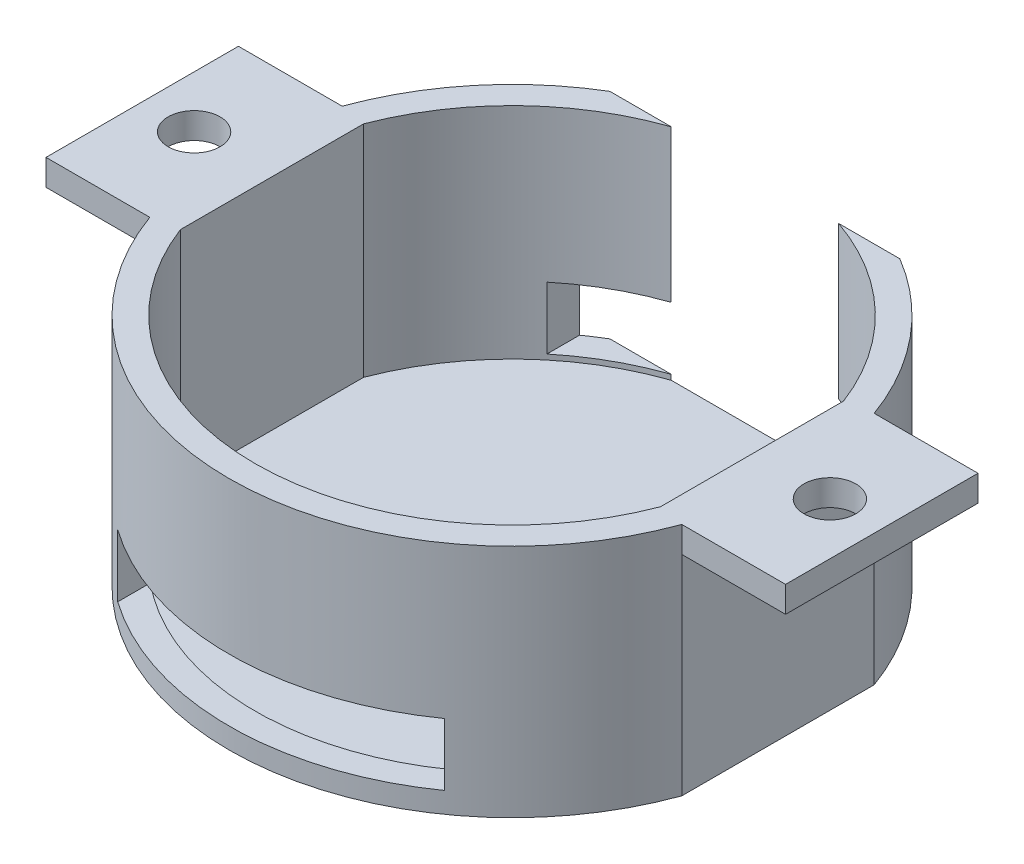
SolidWorks part; units mm, degrees
ref_plane "前视基准面" through (0, 0, 0) normal (0, 0, 1) x (1, 0, 0)
ref_plane "上视基准面" through (0, 0, 0) normal (0, 1, 0) x (1, 0, 0)
ref_plane "右视基准面" through (0, 0, 0) normal (1, 0, 0) x (0, 0, -1)
other "Configuration Table"
sketch "草图1" plane through (0, 0, 0) normal (0, 1, 0) x (1, 0, 0)
  line L0 (0, 0) -> (0, 49.5) construction
  line L1 (-46.25, 17.6405) -> (-46.25, -17.6405)
  line L2 (46.25, 17.6405) -> (46.25, -17.6405)
  line L3 (-51.25, 18.5388) -> (-51.25, -18.5388)
  line L4 (51.25, 18.5388) -> (51.25, -18.5388)
  arc A0 (-51.25, -18.5388) -> (51.25, -18.5388) centre (0, 0) ccw
  arc A1 (-46.25, -17.6405) -> (46.25, -17.6405) centre (0, 0) ccw
  arc A2 (46.25, 17.6405) -> (-46.25, 17.6405) centre (0, 0) ccw
  arc A3 (51.25, 18.5388) -> (-51.25, 18.5388) centre (0, 0) ccw
  dimension "D1" = 109
  dimension "D2" = 99
  dimension "D3" = 92.5
  dimension "D4" = 102.5
extrude "凸台-拉伸1" add sketch "草图1" along normal blind 42.3
ref_plane "基准面1" through (0, 0, 0) normal (0, -1, 0) x (-1, 0, 0)
sketch "草图2" plane through (0, 0, 0) normal (0, -1, 0) x (-1, 0, 0)
  line L0 (51.25, 18.5388) -> (51.25, -18.5388)
  line L1 (0, 54.5) -> (0, 0) construction
  line L2 (-51.25, 18.5388) -> (-51.25, -18.5388)
  circle A0 centre (0, 0) radius 54.5
  dimension "D1" = 109
extrude "凸台-拉伸2" add sketch "草图2" along normal blind 3
ref_plane "基准面3" through (-51.25, 0, 0) normal (-1, 0, 0) x (0, 0, 1)
sketch "草图3" plane through (-51.25, 0, 0) normal (-1, 0, 0) x (0, 0, 1)
  line L0 (18.5388, 42.3) -> (18.5388, -3) construction
  line L1 (-18.5388, 42.3) -> (18.5388, 42.3)
  line L2 (-18.5388, 42.3) -> (-18.5388, 37.3)
  line L3 (-18.5388, 37.3) -> (18.5388, 37.3)
  line L4 (18.5388, 42.3) -> (18.5388, 37.3)
  dimension "D1" = 5
extrude "凸台-拉伸4" add sketch "草图3" along normal blind 20
ref_plane "基准面4" through (51.25, 0, 0) normal (1, 0, 0) x (0, 0, -1)
sketch "草图5" plane through (51.25, 0, 0) normal (1, 0, 0) x (0, 0, -1)
  line L0 (18.5388, 42.3) -> (18.5388, -3) construction
  line L1 (-18.5388, 42.3) -> (18.5388, 42.3)
  line L2 (-18.5388, 42.3) -> (-18.5388, 37.3)
  line L3 (-18.5388, 37.3) -> (18.5388, 37.3)
  line L4 (18.5388, 42.3) -> (18.5388, 37.3)
  dimension "D1" = 5
extrude "凸台-拉伸5" add sketch "草图5" along normal blind 20
ref_plane "基准面5" through (0, 42.3, 0) normal (0, 1, 0) x (1, 0, 0)
sketch "草图6" plane through (0, 42.3, 0) normal (0, 1, 0) x (1, 0, 0)
  line L0 (-61.25, 18.5388) -> (-61.25, -18.5388) construction
  line L1 (-71.25, 18.5388) -> (-51.25, 18.5388) construction
  line L2 (-71.25, -18.5388) -> (-51.25, -18.5388) construction
  line L3 (-71.25, 0) -> (-51.25, 0) construction
  line L4 (-71.25, -18.5388) -> (-71.25, 18.5388) construction
  line L5 (-51.25, 20.3927) -> (-51.25, -20.3927) construction
  circle A0 centre (-61.25, 0) radius 5
  dimension "D1" = 10
extrude "切除-拉伸1" cut sketch "草图6" against normal up to next
cosmetic thread "装饰螺纹线2" parameters "D2"=11
sketch "草图7" plane through (0, 42.3, 0) normal (0, 1, 0) x (1, 0, 0)
  line L0 (51.25, 0) -> (71.25, 0) construction
  line L1 (51.25, -20.3927) -> (51.25, 20.3927) construction
  line L2 (71.25, 18.5388) -> (71.25, -18.5388) construction
  line L3 (61.25, 18.5388) -> (61.25, -18.5388) construction
  line L4 (71.25, 18.5388) -> (51.25, 18.5388) construction
  line L5 (71.25, -18.5388) -> (51.25, -18.5388) construction
  circle A0 centre (61.25, 0) radius 5
  dimension "D1" = 10
extrude "切除-拉伸2" cut sketch "草图7" against normal up to next
cosmetic thread "装饰螺纹线1" parameters "D2"=11
ref_plane "基准面6" through (0, 0, -54.5) normal (0, 0, -1) x (-1, 0, 0)
sketch "草图9" plane through (0, 0, -54.5) normal (0, 0, -1) x (-1, 0, 0)
  line L0 (0, 42.3) -> (0, -34.4098) construction
  line L2 (-31.4775, 1) -> (-31.4775, 13)
  line L3 (-31.4775, 13) -> (31.4775, 13)
  line L4 (31.4775, 13) -> (31.4775, 1)
  line L5 (31.4775, 1) -> (-31.4775, 1)
  line L6 (-55, 0) -> (55, 0) construction
  dimension "D1" = 1
  dimension "D2" = 12
extrude "切除-拉伸3" cut sketch "草图9" against normal through all both and the other way through all
sketch "草图10" plane through (0, -3, 0) normal (0, -1, 0) x (1, 0, 0)
  line L0 (-21.6852, -50) -> (21.6852, -50)
  line L1 (0.4059, -54.5) -> (-35.4371, -54.5)
  line L2 (-24.915, -54.5) -> (24.915, -54.5) construction
  line L3 (-21.6852, -50) -> (-21.6852, -54.5)
  line L4 (21.6852, -50) -> (21.6852, -54.5)
  line L5 (21.6852, -54.5) -> (0.4059, -54.5)
  arc A0 (-51.25, -18.5388) -> (51.25, -18.5388) centre (0, 0) ccw construction
  arc M6 (-51.25, -18.5388) -> (51.25, -18.5388) centre (0, 0) ccw
  dimension "D1" = 4.5
extrude "切除-拉伸4" cut sketch "草图10" against normal through all both and the other way through all contours L0 M6
sketch "草图11" plane through (0, -3, 0) normal (0, -1, 0) x (1, 0, 0)
  line L0 (-27.9258, -46.8017) -> (42.767, -46.8017)
  line L1 (42.767, -46.8017) -> (42.767, -53.8841)
  line L2 (42.767, -53.8841) -> (-27.9258, -53.8841)
  line L3 (-27.9258, -53.8841) -> (-27.9258, -46.8017)
  arc A0 (-51.25, -18.5388) -> (-21.6852, -50) centre (0, 0) ccw construction
extrude "切除-拉伸5" cut sketch "草图11" against normal through all both and the other way through all
